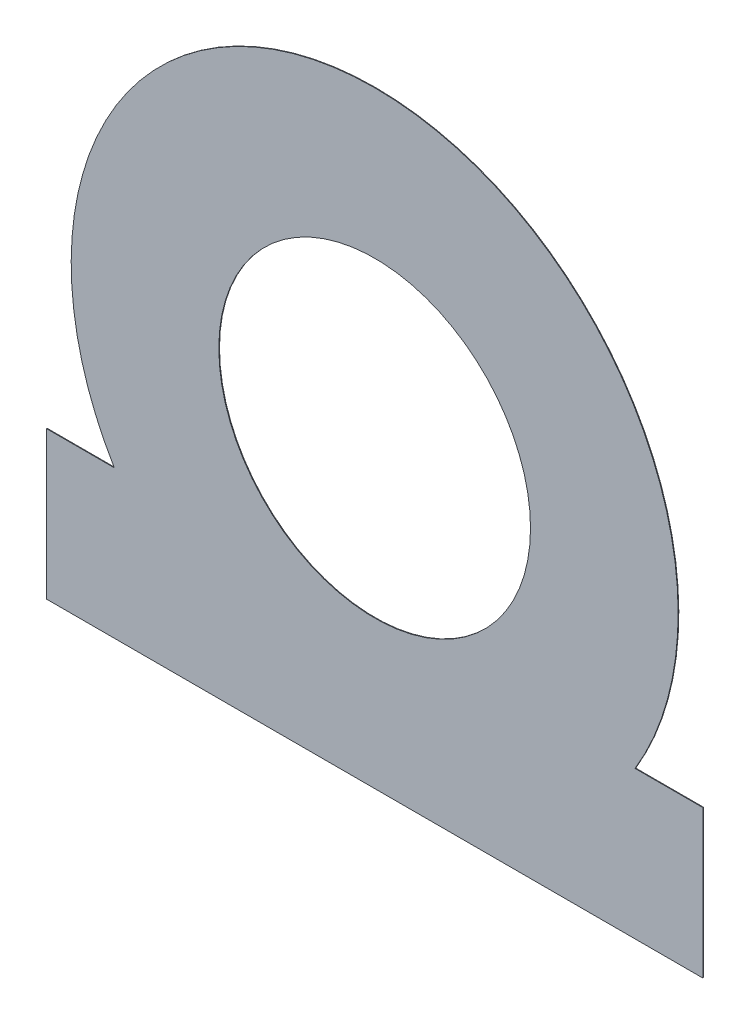
SolidWorks part; units mm, degrees
ref_plane "前视基准面" through (0, 0, 0) normal (0, 0, 1) x (1, 0, 0)
ref_plane "上视基准面" through (0, 0, 0) normal (0, 1, 0) x (1, 0, 0)
ref_plane "右视基准面" through (0, 0, 0) normal (1, 0, 0) x (0, 0, -1)
sketch "草图1" plane through (0, 0, 0) normal (0, 0, 1) x (1, 0, 0)
  line L0 (0, 0) -> (0, -1003.7776) construction
  line L1 (1000, -925) -> (-1000, -925)
  line L2 (1000, -925) -> (1000, -475)
  line L3 (1000, -475) -> (793.7254, -475)
  line L4 (-1000, -925) -> (-1000, -475)
  line L5 (1000, -925) -> (-1000, -475) construction
  line L6 (1000, -475) -> (-1000, -925) construction
  line L7 (-793.7254, -475) -> (-1000, -475)
  circle A0 centre (0, 0) radius 700 construction
  arc A1 (793.7254, -475) -> (-793.7254, -475) centre (0, 0) ccw
  circle A2 centre (0, 0) radius 475
  point P5 (0, -700)
  point P10 (0, 0)
  dimension "D1" = 450
  dimension "D2" = 1400
  dimension "D3" = 225
  dimension "D4" = 450
  dimension "D5" = 2000
extrude "凸台-拉伸1" add sketch "草图1" along normal blind 2
